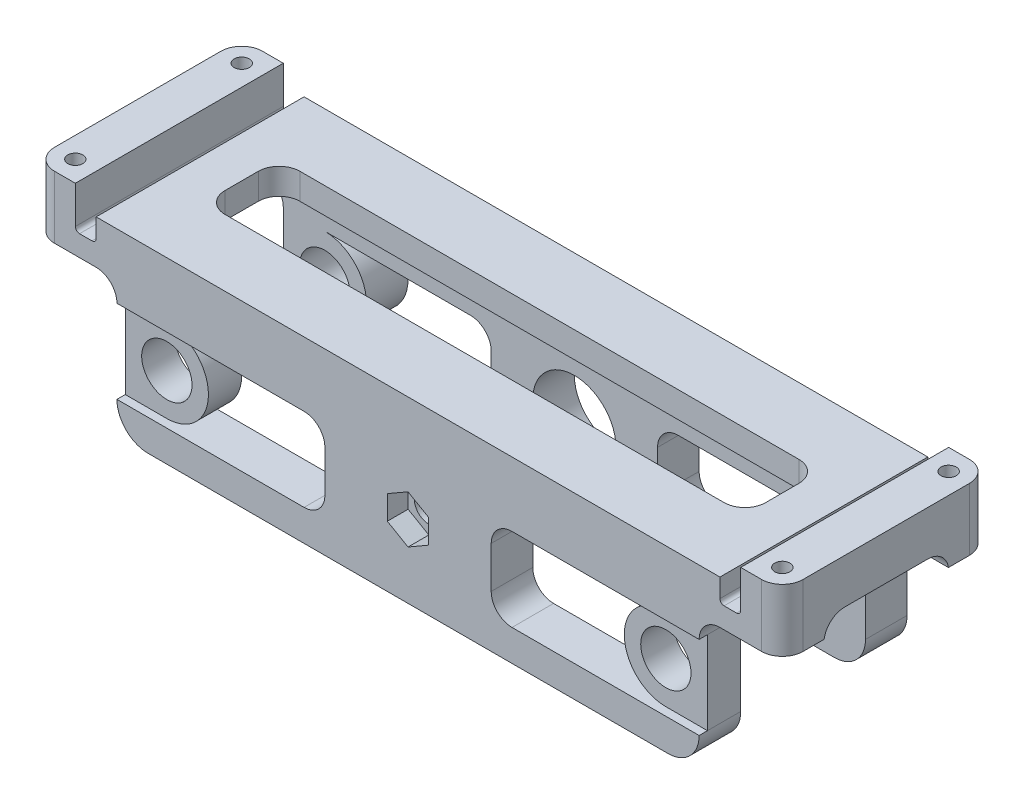
SolidWorks part; units mm, degrees
ref_plane "Front" through (0, 0, 0) normal (0, 0, 1) x (1, 0, 0)
ref_plane "Top" through (0, 0, 0) normal (0, 1, 0) x (1, 0, 0)
ref_plane "Right" through (0, 0, 0) normal (1, 0, 0) x (0, 0, -1)
sketch "Эскиз1" plane through (0, 0, 0) normal (0, 0, 1) x (1, 0, 0)
  line L1 (-75, -25) -> (75, -25)
  line L2 (-75, -25) -> (-75, 25)
  line L3 (-75, 25) -> (75, 25)
  line L4 (75, -25) -> (75, 25)
  line L5 (-75, -25) -> (75, 25) construction
  line L6 (-75, 25) -> (75, -25) construction
  point P0 (0, 0)
extrude "Бобышка-Вытянуть1" add sketch "Эскиз1" along normal blind 10 contours L3 L4 L1 L2
sketch "Эскиз5" plane through (0, 0, 10) normal (0, 0, 1) x (1, 0, 0)
  line L1 (0, 5.75) -> (-4.9796, 2.875)
  line L2 (-4.9796, 2.875) -> (-4.9796, -2.875)
  line L3 (-4.9796, -2.875) -> (0, -5.75)
  line L4 (0, -5.75) -> (4.9796, -2.875)
  line L5 (4.9796, -2.875) -> (4.9796, 2.875)
  line L6 (-75, 25) -> (75, -25) construction
  line L7 (75, 25) -> (-75, -25) construction
  line L8 (4.9796, 2.875) -> (0, 5.75)
  circle A1 centre (0, 0) radius 5.75 construction
  dimension "D1" = 11.5
  dimension "D2" = 9.9593
extrude "Вырез-Вытянуть5" cut sketch "Эскиз5" against normal blind 5
sketch "Эскиз6" plane through (0, 0, 10) normal (0, 0, 1) x (1, 0, 0)
  line L0 (0, 35.2364) -> (0, -37.6455) construction
  line L1 (-81.5914, 0) -> (80.5963, 0) construction
  circle A0 centre (-60, 0) radius 6.05
  circle A1 centre (60, 0) radius 6.05
  dimension "D1" = 60
  dimension "D3" = 12.1
  dimension "D4" = 12.1
  dimension "D2" = 120
extrude "Вырез-Вытянуть6" cut sketch "Эскиз6" against normal through all
sketch "Эскиз7" plane through (0, 0, 10) normal (0, 0, 1) x (1, 0, 0)
  line L0 (65, -25) -> (75, -25)
  line L1 (-65, -25) -> (-25, -25)
  line L2 (-2.5, -44.0947) -> (-2.5, 37.2264) construction
  line L3 (-80.4974, 0) -> (82.7196, 0) construction
  line L4 (-65, -25) -> (-75, -25)
  line L5 (-75, -25) -> (75, -25) construction
  line L6 (-62.5, -17.5) -> (-32.5, -17.5)
  line L7 (27.5, -17.5) -> (-2.5, -17.5)
  line L8 (-75, -25) -> (-75, 25) construction
  line L9 (-75, -25) -> (-75, -15)
  line L10 (-70, -10) -> (-70, 10)
  line L12 (-75, 15) -> (-75, -15)
  line L22 (75, 15) -> (75, -15)
  line L24 (70, -10) -> (70, 10)
  line L25 (75, -25) -> (75, -15)
  line L26 (-2.5, -17.5) -> (-32.5, -17.5)
  line L27 (62.5, -17.5) -> (27.5, -17.5)
  line L28 (-25, -25) -> (25, -25)
  line L29 (65, -25) -> (25, -25)
  arc A1 (-62.5, -17.5) -> (-70, -10) centre (-62.5, -10) cw
  arc A2 (62.5, -17.5) -> (70, -10) centre (62.5, -10) ccw
  arc A4 (-75, 15) -> (-70, 10) centre (-75, 10) cw
  arc A11 (75, 15) -> (70, 10) centre (75, 10) ccw
  point P71 (67.5, 15)
  dimension "D5" = 7.5
  dimension "D9" = 5
  dimension "D1" = 5
  dimension "D2" = 5
extrude "Вырез-Вытянуть7" cut sketch "Эскиз7" against normal through all
sketch "Эскиз8" plane through (0, 0, 0) normal (0, 0, -1) x (-1, 0, 0)
  line L0 (-78.922, 0) -> (76.8097, 0) construction
  line L1 (0, -33.7328) -> (0, 41.5826) construction
  line L2 (20, -5) -> (20, 5)
  line L3 (45, 10) -> (25, 10)
  line L4 (-45, -10) -> (-25, -10)
  line L5 (45, -10) -> (25, -10)
  line L6 (-62.5, -17.5) -> (62.5, -17.5) construction
  line L7 (-45, 10) -> (-25, 10)
  line L8 (-20, -5) -> (-20, 5)
  arc A0 (60, 10) -> (60, -10) centre (60, 0) ccw
  arc A1 (20, -5) -> (25, -10) centre (25, -5) ccw
  arc A2 (20, 5) -> (25, 10) centre (25, 5) cw
  arc A3 (-20, 5) -> (-25, 10) centre (-25, 5) ccw
  arc A4 (-20, -5) -> (-25, -10) centre (-25, -5) cw
  arc A5 (-60, 10) -> (-60, -10) centre (-60, 0) cw
  spline S0 degree 3 poles (60, -10) (59.9555, -10) (54.1279, -10) (45, -10) knots 0 0 0 0 1 1 1 1
  spline S1 degree 3 poles (60, 10) (59.9555, 10) (54.1279, 10) (45, 10) knots 0 0 0 0 1 1 1 1
  spline S2 degree 3 poles (-60, 10) (-59.9555, 10) (-54.1279, 10) (-45, 10) knots 0 0 0 0 1 1 1 1
  spline S3 degree 3 poles (-60, -10) (-59.9555, -10) (-54.1279, -10) (-45, -10) knots 0 0 0 0 1 1 1 1
  point P11 (20, 0)
  point P31 (-20, 0)
  dimension "D1" = 7.5
  dimension "D2" = 5
  dimension "D3" = 10
  dimension "D4" = 40
extrude "Вырез-Вытянуть8" cut sketch "Эскиз8" against normal through all
sketch "Эскиз9" plane through (0, 0, 5) normal (0, 0, 1) x (1, 0, 0)
  circle A0 centre (0, 0) radius 3.5
extrude "Вырез-Вытянуть9" cut sketch "Эскиз9" against normal through all
sketch "Эскиз10" plane through (0, 0, 10) normal (0, 0, 1) x (1, 0, 0)
  line L0 (75, 15) -> (75, 25) construction
  line L1 (-75, 25) -> (75, 25)
  line L2 (-75, 25) -> (-75, 23.5)
  line L3 (-75, 23.5) -> (75, 23.5)
  line L4 (75, 25) -> (75, 23.5)
  dimension "D1" = 1.5
extrude "Вырез-Вытянуть10" cut sketch "Эскиз10" against normal through all
ref_plane "Плоскость1" through (0, 0, -15) normal (0, 0, -1) x (-1, 0, 0)
sketch "Эскиз11" plane through (0, 0, 0) normal (0, 0, -1) x (-1, 0, 0)
  line L0 (-75, 15) -> (-75, 23.5) construction
  line L1 (75, 23.5) -> (-75, 23.5)
  line L2 (75, 23.5) -> (75, 19.25)
  line L3 (75, 19.25) -> (-75, 19.25)
  line L4 (-75, 23.5) -> (-75, 19.25)
extrude "Бобышка-Вытянуть3" add sketch "Эскиз11" along normal blind 15
mirror "Зеркальное отражение9" about plane through (0, 0, -15) normal (0, 0, -1) of bodies 136
sketch "Эскиз14" plane through (0, 0, -40) normal (0, 0, -1) x (-1, 0, 0)
  circle A0 centre (0, 0) radius 10
  dimension "D1" = 20
extrude "Вырез-Вытянуть12" cut sketch "Эскиз14" against normal up to next
sketch "Эскиз15" plane through (0, 19.25, 0) normal (0, -1, 0) x (1, 0, 0)
  line L0 (-35.3114, -15) -> (35.3114, -15) construction
  line L1 (-65, -24) -> (65, -24)
  line L2 (-65, -24) -> (-65, -6)
  line L3 (-65, -6) -> (65, -6)
  line L4 (65, -24) -> (65, -6)
  line L5 (-65, -24) -> (65, -6) construction
  line L6 (-65, -6) -> (65, -24) construction
  point P0 (0, -15)
extrude "Вырез-Вытянуть13" cut sketch "Эскиз15" against normal through all
fillet "Скругление1" radius 5 4 edges at (65, 21.375, -24) (65, 21.375, -6) (-65, 21.375, -6) (-65, 21.375, -24)
sketch "Эскиз18" plane through (75, 0, 0) normal (1, 0, 0) x (0, 0, -1)
  line L0 (-10, 23.5) -> (-10, 15)
  line L1 (-10, 15) -> (0, 15)
  line L2 (0, 15) -> (0, 19.25)
  line L3 (0, 19.25) -> (30, 19.25)
  line L4 (30, 19.25) -> (30, 15)
  line L5 (30, 15) -> (40, 15)
  line L6 (40, 15) -> (40, 25)
  line L7 (40, 25) -> (-10, 25)
  line L8 (-10, 25) -> (-10, 23.5)
extrude "Бобышка-Вытянуть4" add sketch "Эскиз18" along normal blind 15
sketch "Эскиз19" plane through (-75, 0, 0) normal (-1, 0, 0) x (0, 0, 1)
  line L0 (-40, 15) -> (-30, 15)
  line L1 (-30, 15) -> (-30, 19.25)
  line L2 (-30, 19.25) -> (0, 19.25)
  line L3 (0, 19.25) -> (0, 15)
  line L4 (0, 15) -> (0, 19.25) construction
  line L5 (0, 15) -> (10, 15)
  line L6 (10, 15) -> (10, 25)
  line L7 (10, 25) -> (-40, 25)
  line L8 (-40, 25) -> (-40, 15)
extrude "Бобышка-Вытянуть5" add sketch "Эскиз19" along normal blind 15
fillet "Скругление2" radius 5 4 edges at (-90, 20, -40) (-90, 20, 10) (90, 20, 10) (90, 20, -40)
hole_wizard "Цековка для винта с заклепочной головкой M31" positions "Трехмерный эскиз1" profile "Эскиз20" counterbore size "M3" standard "Ansi Metric"
sketch3d "Трехмерный эскиз1"
  line L0 (-85, 15, -35) -> (-85, 25, -35) construction
  line L1 (-85, 25, 5) -> (-85, 15, 5) construction
  line L2 (85, 25, -35) -> (85, 15, -35) construction
  line L3 (85, 15, 5) -> (85, 25, 5) construction
  arc A0 (85, 15, -40) -> (90, 15, -35) centre (85, 15, -35) ccw construction
  point P0 (-85, 15, -35)
  point P4 (-85, 15, 5)
  point P8 (83.0866, 15, -39.6194)
  point P13 (85, 10, -35)
  point P14 (85, 15, -35)
  point P18 (85, 15, 5)
sketch "Эскиз20" plane through (-85, 15, -35) normal (1, 0, 0) x (0, 0, -1)
  line L0 (0, 0) -> (0, 10)
  line L1 (1.8, 9.975) -> (1.825, 10)
  line L2 (1.8, 9.975) -> (1.8, 2.425)
  line L3 (1.8, 2.425) -> (1.825, 2.4)
  line L4 (1.825, 2.4) -> (3.5, 2.4)
  line L5 (3.5, 2.4) -> (3.5, 0.025)
  line L6 (3.5, 0.025) -> (3.525, 0)
  line L7 (3.525, 0) -> (0, 0)
  line L8 (-3.5, 0.025) -> (-3.525, 0) construction
  line L9 (-1.8, 2.425) -> (-1.825, 2.4) construction
  line L11 (0, -6.35) -> (0, 107.95) construction
  line L12 (1.825, 10) -> (0, 10)
  line L13 (-1.8, 9.975) -> (-1.825, 10) construction
  dimension "Диаметр сквозного отверстия" = 3.6
  dimension "Глубина сквозного отверстия" = 10
  dimension "Диаметр цековки" = 7
  dimension "Глубина цековки" = 2.4
  dimension "Диаметр передней зенковки" = 7.05
  dimension "Угол передней зенковки" = 90
  dimension "Диаметр средней зенковки" = 3.65
  dimension "Угол средней зенковки" = 90
  dimension "Диаметр задней зенковки" = 3.65
  dimension "Угол задней зенковки" = 90
sketch "Эскиз21" plane through (0, 0, 10) normal (0, 0, 1) x (1, 0, 0)
  line L0 (0, 29.37) -> (0, -26.0574) construction
  line L1 (-60, 10) -> (-70, 10)
  line L2 (-70, 10) -> (-70, -10)
  line L3 (-70, -10) -> (-60, -10)
  line L4 (60, 10) -> (70, 10)
  line L5 (70, 10) -> (70, -10) construction
  line L6 (70, 10) -> (70, -10)
  line L7 (70, -10) -> (60, -10)
  arc A0 (-70, 10) -> (-75, 15) centre (-75, 10) ccw construction
  arc A1 (-60, -10) -> (-60, 10) centre (-60, 0) ccw
  arc A2 (60, -10) -> (60, 10) centre (60, 0) cw
extrude "Вырез-Вытянуть20" cut sketch "Эскиз21" against normal blind 2
sketch "Эскиз22" plane through (0, 25, 0) normal (0, 1, 0) x (1, 0, 0)
  line L0 (85, -10) -> (75, -10) construction
  line L1 (75, 40) -> (80, 40)
  line L2 (75, 40) -> (75, -10)
  line L3 (75, -10) -> (80, -10)
  line L4 (80, 40) -> (80, -10)
  line L5 (0, 46.2275) -> (0, -23.9781) construction
  line L6 (-80, 40) -> (-80, -10)
  line L7 (-75, -10) -> (-80, -10)
  line L8 (-75, 40) -> (-75, -10)
  line L9 (-75, 40) -> (-80, 40)
extrude "Вырез-Вытянуть21" cut sketch "Эскиз22" against normal blind 5
fillet "Скругление3" radius 1 4 edges at (75, 20, -15) (80, 20, -15) (-75, 20, -15) (-80, 20, -15)
fillet "Скругление4" radius 5 10 edges at (82.5, 15, 0) (82.5, 15, -30) (90, 17.125, 0) (90, 17.125, -30) (-82.5, 15, -30) (-82.5, 15, 0) (-90, 17.125, -30) (-90, 17.125, 0)
sketch "Эскиз23" plane through (0, 25, 0) normal (0, 1, 0) x (1, 0, 0)
  line L0 (-80, 40) -> (-80, -10)
  line L1 (-80, -10) -> (-85, -10)
  line L2 (-80, 40) -> (-85, 40)
  line L3 (-90, -5) -> (-90, 35)
  line L4 (80, 40) -> (80, -10)
  line L5 (80, -10) -> (85, -10)
  line L6 (90, -5) -> (90, 35)
  line L7 (80, 40) -> (85, 40)
  line L8 (80, -10) -> (85, -10)
  arc A0 (-90, 35) -> (-85, 40) centre (-85, 35) cw
  arc A1 (-85, -10) -> (-90, -5) centre (-85, -5) cw
  arc A2 (85, -10) -> (90, -5) centre (85, -5) ccw
  arc A3 (85, 40) -> (90, 35) centre (85, 35) cw
  circle A4 centre (85, 35) radius 1.825
  circle A5 centre (85, -5) radius 1.825
  circle A6 centre (-85, 35) radius 1.825
  circle A7 centre (-85, -5) radius 1.825
extrude "Бобышка-Вытянуть7" add sketch "Эскиз23" along normal blind 5 contours A3 L7 L4 L5 A2 L6 A5 A4
sketch "Эскиз24" plane through (0, 23.5, 0) normal (0, 1, 0) x (1, 0, 0)
  line L1 (-75, 40) -> (75, 40)
  line L2 (-75, 40) -> (-75, -10)
  line L3 (-75, -10) -> (75, -10)
  line L4 (75, 40) -> (75, -10)
  line L5 (-60, 24) -> (60, 24)
  line L6 (-65, 19) -> (-65, 11)
  line L7 (-60, 6) -> (60, 6)
  line L8 (65, 19) -> (65, 11)
  arc A0 (60, 6) -> (65, 11) centre (60, 11) ccw
  arc A1 (60, 24) -> (65, 19) centre (60, 19) cw
  arc A2 (-60, 6) -> (-65, 11) centre (-60, 11) cw
  arc A3 (-60, 24) -> (-65, 19) centre (-60, 19) ccw
  dimension "D1" = 5
extrude "Бобышка-Вытянуть8" add sketch "Эскиз24" along normal blind 2
